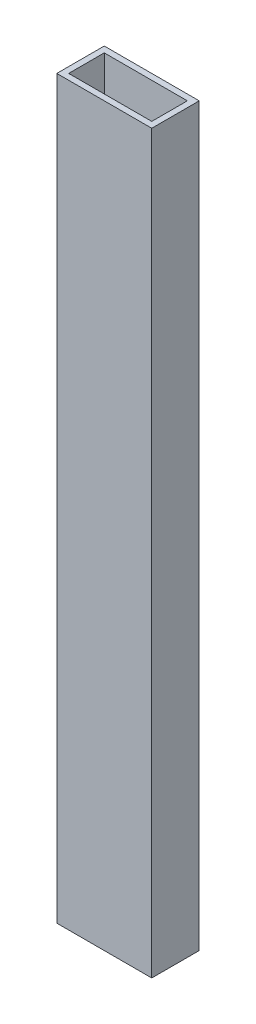
SolidWorks part; units mm, degrees
material "6061-T6 (SS)"
ref_plane "Front Plane" through (0, 0, 0) normal (0, 0, 1) x (1, 0, 0)
ref_plane "Top Plane" through (0, 0, 0) normal (0, 1, 0) x (1, 0, 0)
ref_plane "Right Plane" through (0, 0, 0) normal (1, 0, 0) x (0, 0, -1)
sketch "Sketch1" plane through (0, 0, 0) normal (0, 1, 0) x (1, 0, 0)
  line L1 (-22.225, 9.525) -> (22.225, 9.525)
  line L2 (-22.225, 9.525) -> (-22.225, -9.525)
  line L3 (-22.225, -9.525) -> (22.225, -9.525)
  line L4 (22.225, 9.525) -> (22.225, -9.525)
  line L5 (-22.225, 9.525) -> (22.225, -9.525) construction
  line L6 (-22.225, -9.525) -> (22.225, 9.525) construction
  line L7 (-25.4, 12.7) -> (25.4, 12.7)
  line L8 (-25.4, 12.7) -> (-25.4, -12.7)
  line L9 (-25.4, -12.7) -> (25.4, -12.7)
  line L10 (25.4, 12.7) -> (25.4, -12.7)
  line L11 (-25.4, 12.7) -> (25.4, -12.7) construction
  line L12 (-25.4, -12.7) -> (25.4, 12.7) construction
  point P0 (0, 0)
  point P6 (0, 0)
  dimension "D1" = 50.8
  dimension "D2" = 25.4
  dimension "D3" = 44.45
  dimension "D4" = 19.05
extrude "Boss-Extrude1" add sketch "Sketch1" along normal mid plane 393.7
